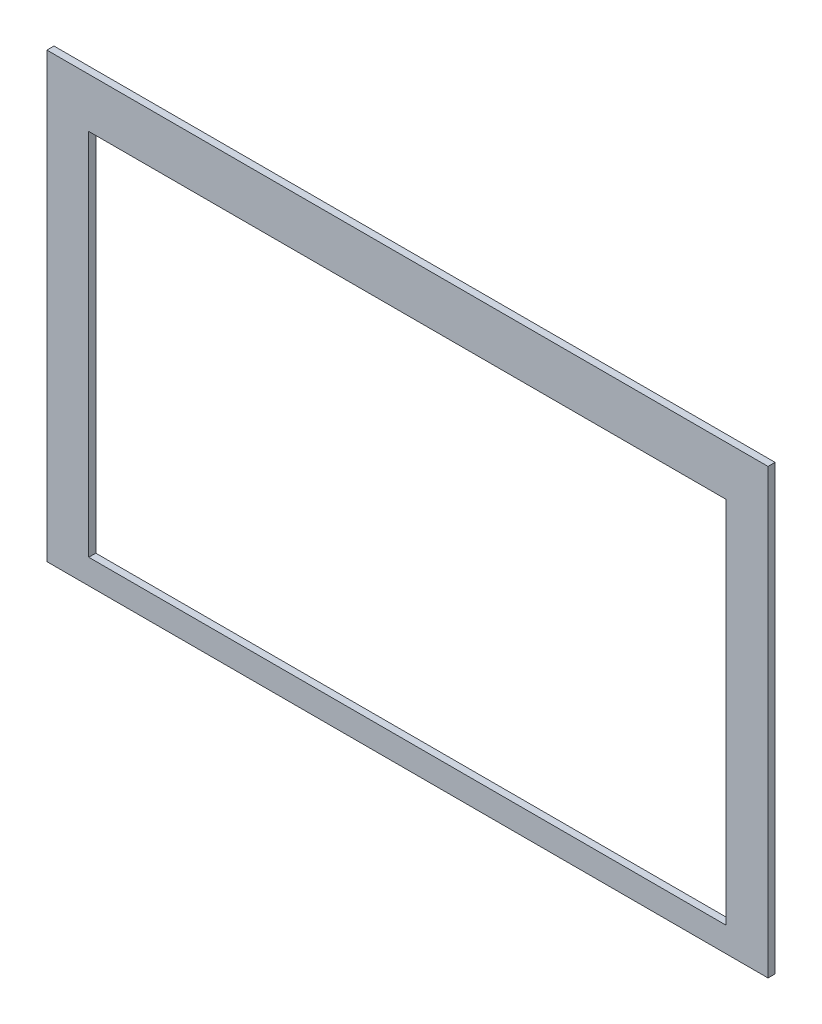
SolidWorks part; units mm, degrees
ref_plane "Front" through (0, 0, 0) normal (0, 0, 1) x (1, 0, 0)
ref_plane "Top" through (0, 0, 0) normal (0, 1, 0) x (1, 0, 0)
ref_plane "Right" through (0, 0, 0) normal (1, 0, 0) x (0, 0, -1)
sketch "Эскиз1" plane through (0, 0, 0) normal (0, 0, 1) x (1, 0, 0)
  line L1 (750.9118, 514.6067) -> (1362.9118, 514.6067)
  line L2 (750.9118, 514.6067) -> (750.9118, 138.6067)
  line L3 (750.9118, 138.6067) -> (1362.9118, 138.6067)
  line L4 (1362.9118, 514.6067) -> (1362.9118, 138.6067)
  dimension "D1" = 612
  dimension "D2" = 376
extrude "Бобышка-Вытянуть1" add sketch "Эскиз1" along normal blind 6
sketch "Эскиз2" plane through (0, 0, 6) normal (0, 0, 1) x (1, 0, 0)
  line L0 (1056.9118, 514.6067) -> (1056.9118, 138.6067) construction
  line L1 (786.4118, 472.6067) -> (1327.4118, 472.6067)
  line L2 (786.4118, 472.6067) -> (786.4118, 159.6067)
  line L3 (786.4118, 159.6067) -> (1327.4118, 159.6067)
  line L4 (1327.4118, 472.6067) -> (1327.4118, 159.6067)
  line L5 (1362.9118, 514.6067) -> (750.9118, 514.6067) construction
  line L6 (750.9118, 138.6067) -> (1362.9118, 138.6067) construction
  point P10 (1056.9118, 472.6067)
  dimension "D1" = 313
  dimension "D2" = 541
  dimension "D3" = 21
extrude "Вырез-Вытянуть1" cut sketch "Эскиз2" against normal up to surface (6 mm away) up to face at (1056.9118, 326.6067, 0)
